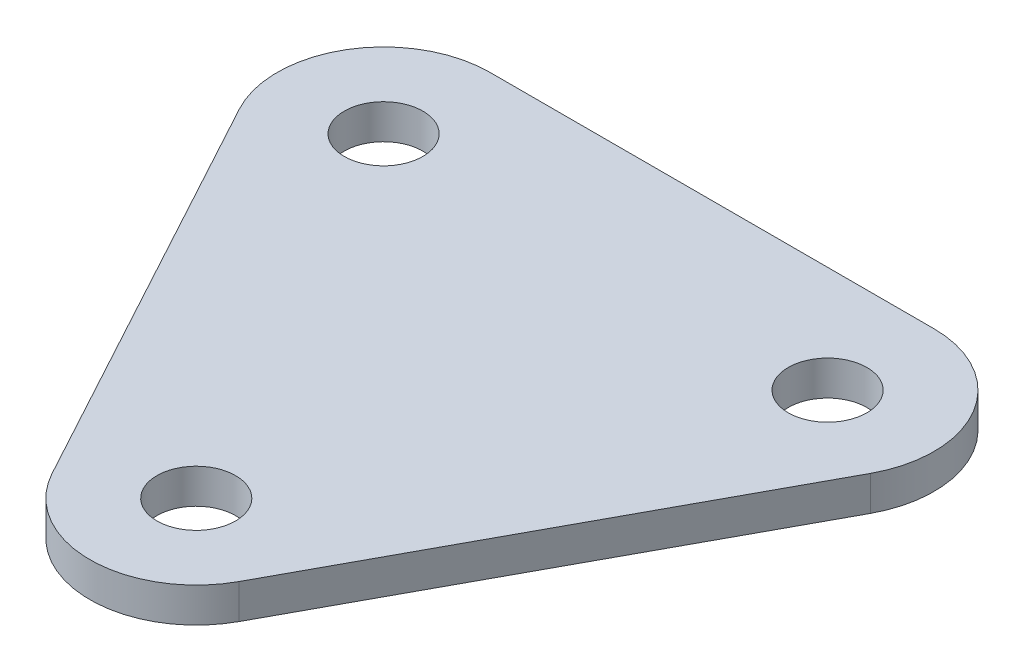
SolidWorks part; units mm, degrees
ref_plane "Front Plane" through (0, 0, 0) normal (0, 0, 1) x (1, 0, 0)
ref_plane "Top Plane" through (0, 0, 0) normal (0, 1, 0) x (1, 0, 0)
ref_plane "Right Plane" through (0, 0, 0) normal (1, 0, 0) x (0, 0, -1)
sketch "Sketch2" plane through (0, 0, 0) normal (0, 1, 0) x (1, 0, 0)
  line L0 (0, 110.3481) -> (0, -110.3481) construction
  line L1 (-48, 61.0594) -> (48, 61.0594)
  line L2 (68.2177, 27.0939) -> (20.2177, -61.4061)
  line L3 (0, -72.3407) -> (0, -58.9406)
  line L4 (0, -43.0405) -> (0, 61.0594)
  line L5 (-68.2177, 27.0939) -> (-20.2177, -61.4061)
  line L6 (-48, 38.0594) -> (48, 38.0594) construction
  arc A0 (48, 61.0594) -> (68.2177, 27.0939) centre (48, 38.0594) cw
  arc A1 (20.2177, -61.4061) -> (-20.2177, -61.4061) centre (0, -50.4406) cw
  circle A2 centre (48, 38.0594) radius 8.5
  circle A3 centre (0, -50.4406) radius 8.5
  circle A4 centre (-48, 38.0594) radius 8.5
  arc A5 (-48, 61.0594) -> (-68.2177, 27.0939) centre (-48, 38.0594) ccw
  point P3 (0, 0)
  dimension "D2" = 46
  dimension "D3" = 23
  dimension "D5" = 8.5
  dimension "D6" = 17
  dimension "D1" = 48
  dimension "D4" = 88.5
extrude "Boss-Extrude1" add sketch "Sketch2" along normal blind 7.5 contours L1 A5 L5 A1 L3 A3 L4 A4 | A3 L3 A1 L2 A0 L1 L4 A2
